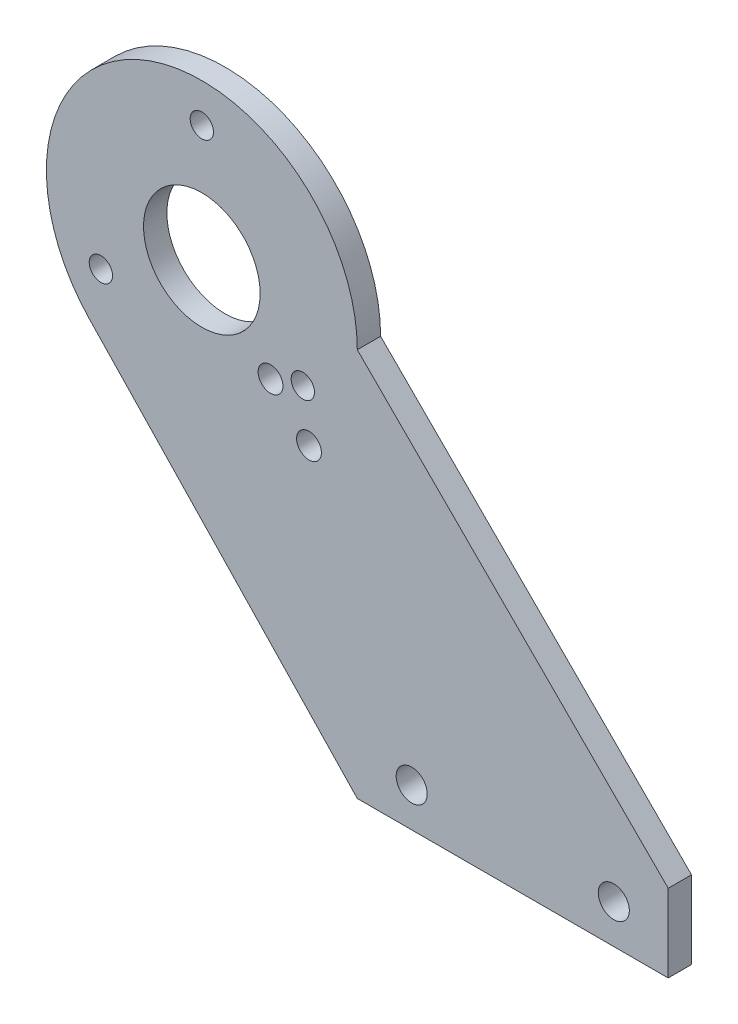
SolidWorks part; units mm, degrees
material "6061 Alloy"
ref_plane "Front Plane" through (0, 0, 0) normal (0, 0, 1) x (1, 0, 0)
ref_plane "Top Plane" through (0, 0, 0) normal (0, 1, 0) x (1, 0, 0)
ref_plane "Right Plane" through (0, 0, 0) normal (1, 0, 0) x (0, 0, -1)
sketch "Sketch1" plane through (0, 0, 0) normal (0, 0, 1) x (1, 0, 0)
  line L0 (20, -50) -> (-14.4828, -13.7931)
  line L1 (20, -40) -> (60, -40) construction
  line L2 (20, -40) -> (20, -50) construction
  line L3 (20, -50) -> (60, -50)
  line L4 (60, -40) -> (60, -50)
  line L5 (20, 0) -> (60, -40)
  line L6 (60.5465, 52.4536) -> (-8.9071, 17.9071)
  line L8 (70.7122, 35.292) -> (20, 0)
  arc A0 (20, 0) -> (-8.9071, 17.9071) centre (0, 0) ccw construction
  arc A1 (-14.4828, -13.7931) -> (20, 0) centre (0, 0) ccw construction
  circle A2 centre (0, 0) radius 7.5
  arc A3 (70.7122, 35.292) -> (60.5465, 52.4536) centre (65, 43.5) ccw
  circle A4 centre (65, 43.5) radius 4
  arc A5 (60.5465, 52.4536) -> (70.7122, 35.292) centre (65, 43.5) ccw construction
  circle A6 centre (0, 0) radius 20 construction
  arc A7 (-8.9071, 17.9071) -> (-14.4828, -13.7931) centre (0, 0) ccw
  arc A8 (70.2963, 35.0177) -> (60.5465, 52.4536) centre (65, 43.5) ccw construction
  arc A9 (60.5465, 52.4536) -> (70.2963, 35.0177) centre (65, 43.5) ccw construction
  dimension "D1" = 40
  dimension "8" = 15
  dimension "D7" = 20
  dimension "D8" = 43.5
  dimension "D10" = 8
  dimension "D2" = 50
  dimension "D3" = 20
  dimension "D4" = 10
  dimension "D5" = 40
  dimension "D9" = 65
extrude "Boss-Extrude1" add sketch "Sketch1" along normal blind 3
sketch "Sketch2" plane through (0, 0, 0) normal (0, 0, 1) x (1, 0, 0)
  line L0 (0, 0) -> (50, -50) construction
  line L1 (20, -50) -> (60, -50) construction
  line L2 (60, -40) -> (20, 0) construction
  circle A0 centre (0, 0) radius 15 construction
  circle A1 centre (0, 15) radius 1.5
  circle A2 centre (12.9904, -7.5) radius 1.5
  circle A3 centre (-12.9904, -7.5) radius 1.5
  circle A4 centre (13.7886, -13.7886) radius 1.6
  circle A5 centre (8.8388, -8.8388) radius 1.6
  point P12 (0, 0)
  dimension "D1" = 30
  dimension "D2" = 3
  dimension "D4" = 19.5
  dimension "D5" = 3.2
  dimension "D6" = 3.2
  dimension "D7" = 12.5
  dimension "D3" = 3
extrude "Cut-Extrude1" cut sketch "Sketch2" along normal through all both and the other way through all
sketch "Sketch4" plane through (0, 0, 0) normal (0, 0, 1) x (1, 0, 0)
  line L0 (20, -45) -> (60, -45) construction
  line L1 (60, -50) -> (60, -40) construction
  line L2 (20, -50) -> (60, -50) construction
  line L3 (20, -45) -> (20, -50) construction
  line L4 (40, -45) -> (40, -50) construction
  circle A0 centre (27, -45) radius 2
  circle A1 centre (53, -45) radius 2
  point P7 (40, -45)
  dimension "D1" = 4
  dimension "D2" = 13
  dimension "D3" = 5
extrude "Cut-Extrude3" cut sketch "Sketch4" along normal through all both and the other way through all
sketch "Sketch5" plane through (0, 0, 0) normal (0, 0, 1) x (1, 0, 0)
  line L5 (60.5465, 52.4536) -> (-8.9071, 17.9071)
  line L6 (65, 43.5) -> (60.5465, 52.4536) construction
  line L7 (60.5465, 52.4536) -> (-8.9071, 17.9071) construction
  line L8 (20, 0) -> (70.7122, 35.292)
  arc A0 (70.7122, 35.292) -> (60.5465, 52.4536) centre (65, 43.5) ccw
  arc A1 (20, 0) -> (-8.9071, 17.9071) centre (0, 0) ccw
extrude "Cut-Extrude4" cut sketch "Sketch5" along normal blind 10
fillet "Fillet2" [suppressed] radius 10
sketch "Sketch3" [suppressed] plane through (0, 0, 0) normal (0, 0, 1) x (1, 0, 0)
  circle A0 centre (65, 37.5) radius 15 construction
  circle A1 centre (65, 52.5) radius 1.5
  circle A2 centre (77.9904, 30) radius 1.5
  circle A3 centre (52.0096, 30) radius 1.5
  dimension "D1" = 3
  dimension "D2" = 30
  dimension "D3" = 3
extrude "Cut-Extrude2" [suppressed] cut sketch "Sketch3" along normal through all both and the other way through all
